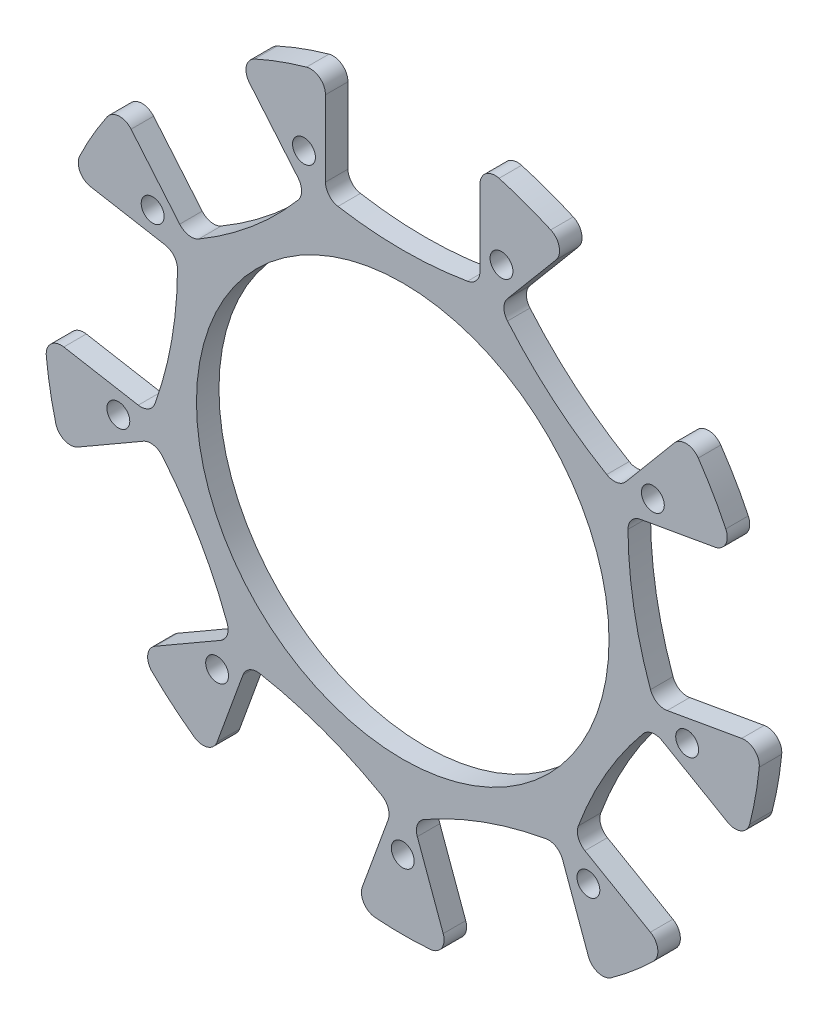
SolidWorks part; units mm, degrees
material "ｱｸﾘﾙ (中-上級の耐衝撃性)"
ref_plane "正面" through (0, 0, 0) normal (0, 0, 1) x (1, 0, 0)
ref_plane "平面" through (0, 0, 0) normal (0, 1, 0) x (1, 0, 0)
ref_plane "右側面" through (0, 0, 0) normal (1, 0, 0) x (0, 0, -1)
sketch "ｽｹｯﾁ1" plane through (0, 0, 0) normal (0, 0, 1) x (1, 0, 0)
  circle A0 centre (0, 0) radius 47.75
  dimension "D1" = 95.5
extrude "ﾎﾞｽ - 押し出し1" add sketch "ｽｹｯﾁ1" along normal blind 3
sketch "ｽｹｯﾁ2" plane through (0, 0, 3) normal (0, 0, 1) x (1, 0, 0)
  line L2 (0, 47.75) -> (0, -47.75) construction
  line L3 (-10.3, 46.6259) -> (-10.3, 32.3257)
  line L8 (22.0803, 42.3382) -> (12.8883, 31.3836)
  line L9 (37.8608, 29.0968) -> (28.6688, 18.1422)
  line L12 (10.3, 46.6259) -> (10.3, 32.3257)
  line L13 (0, 31.28) -> (0, 41.18) construction
  line L94 (44.1289, 18.24) -> (30.046, 15.7568)
  line L95 (47.7061, -2.047) -> (33.6232, -4.5302)
  line L96 (45.5292, -14.3929) -> (33.1449, -7.2428)
  line L97 (35.2292, -32.233) -> (22.8449, -25.0829)
  line L98 (25.6258, -40.2912) -> (20.7349, -26.8534)
  line L99 (6.2682, -47.3368) -> (1.3772, -33.899)
  line L100 (-6.2682, -47.3368) -> (-1.3772, -33.899)
  line L101 (-25.6258, -40.2912) -> (-20.7349, -26.8534)
  line L102 (-35.2292, -32.233) -> (-22.8449, -25.0829)
  line L103 (-45.5292, -14.3929) -> (-33.1449, -7.2428)
  line L104 (-47.7061, -2.047) -> (-33.6232, -4.5302)
  line L105 (-44.1289, 18.24) -> (-30.046, 15.7568)
  line L106 (-37.8608, 29.0968) -> (-28.6688, 18.1422)
  line L107 (-22.0803, 42.3382) -> (-12.8883, 31.3836)
  circle A0 centre (0, 0) radius 47.75 construction
  arc A1 (-10.3, 46.6259) -> (10.3, 46.6259) centre (0, 0) cw
  arc A2 (-10.3, 32.3257) -> (10.3, 32.3257) centre (0, 82.53) ccw
  arc A19 (22.0803, 42.3382) -> (37.8608, 29.0968) centre (0, 0) cw
  arc A20 (12.8883, 31.3836) -> (28.6688, 18.1422) centre (53.0493, 63.2216) ccw
  arc A21 (44.1289, 18.24) -> (47.7061, -2.047) centre (0, 0) cw
  arc A22 (30.046, 15.7568) -> (33.6232, -4.5302) centre (81.2762, 14.3312) ccw
  arc A23 (45.5292, -14.3929) -> (35.2292, -32.233) centre (0, 0) cw
  arc A24 (33.1449, -7.2428) -> (22.8449, -25.0829) centre (71.4731, -41.265) ccw
  arc A25 (25.6258, -40.2912) -> (6.2682, -47.3368) centre (0, 0) cw
  arc A26 (20.7349, -26.8534) -> (1.3772, -33.899) centre (28.2269, -77.5528) ccw
  arc A27 (-6.2682, -47.3368) -> (-25.6258, -40.2912) centre (0, 0) cw
  arc A28 (-1.3772, -33.899) -> (-20.7349, -26.8534) centre (-28.2269, -77.5528) ccw
  arc A29 (-35.2292, -32.233) -> (-45.5292, -14.3929) centre (0, 0) cw
  arc A30 (-22.8449, -25.0829) -> (-33.1449, -7.2428) centre (-71.4731, -41.265) ccw
  arc A31 (-47.7061, -2.047) -> (-44.1289, 18.24) centre (0, 0) cw
  arc A32 (-33.6232, -4.5302) -> (-30.046, 15.7568) centre (-81.2762, 14.3312) ccw
  arc A33 (-37.8608, 29.0968) -> (-22.0803, 42.3382) centre (0, 0) cw
  arc A34 (-28.6688, 18.1422) -> (-12.8883, 31.3836) centre (-53.0493, 63.2216) ccw
  point P11 (0, 41.18)
  point P58 (0, 0)
  dimension "D2" = 51.25
  dimension "D5" = 20.6
  dimension "D4" = 82.53
  dimension "D1" = 41.18
  dimension "D3" = 9.9
  dimension "D6" = 9
extrude "ｶｯﾄ - 押し出し1" cut sketch "ｽｹｯﾁ2" against normal through all
sketch "ｽｹｯﾁ3" plane through (0, 0, 3) normal (0, 0, 1) x (1, 0, 0)
  line L0 (0, 0) -> (0, -38.5) construction
  line L1 (0, 0) -> (-24.7473, -29.4927) construction
  line L2 (0, 0) -> (-37.9151, -6.6855) construction
  line L3 (0, 0) -> (-33.342, 19.25) construction
  line L4 (0, 0) -> (-13.1678, 36.1782) construction
  line L5 (0, 0) -> (13.1678, 36.1782) construction
  line L6 (0, 0) -> (33.342, 19.25) construction
  line L7 (0, 0) -> (37.9151, -6.6855) construction
  line L8 (0, 0) -> (24.7473, -29.4927) construction
  circle A2 centre (0, -38.5) radius 1.525
  circle A3 centre (0, 0) radius 38.5 construction
  circle A4 centre (-24.7473, -29.4927) radius 1.525
  circle A5 centre (0, 0) radius 38.5 construction
  circle A6 centre (-37.9151, -6.6855) radius 1.525
  circle A7 centre (0, 0) radius 38.5 construction
  circle A8 centre (-33.342, 19.25) radius 1.525
  circle A9 centre (0, 0) radius 38.5 construction
  circle A10 centre (-13.1678, 36.1782) radius 1.525
  circle A11 centre (0, 0) radius 38.5 construction
  circle A12 centre (13.1678, 36.1782) radius 1.525
  circle A13 centre (0, 0) radius 38.5 construction
  circle A14 centre (33.342, 19.25) radius 1.525
  circle A15 centre (0, 0) radius 38.5 construction
  circle A16 centre (37.9151, -6.6855) radius 1.525
  circle A17 centre (0, 0) radius 38.5 construction
  circle A18 centre (24.7473, -29.4927) radius 1.525
  circle A19 centre (0, 0) radius 38.5 construction
  point P10 (0, 0)
  point P32 (0, 0)
  dimension "D1" = 3.05
  dimension "D2" = 77
  dimension "D3" = 9
extrude "ｶｯﾄ - 押し出し2" cut sketch "ｽｹｯﾁ3" against normal through all
sketch "ｽｹｯﾁ4" plane through (0, 0, 0) normal (0, 0, -1) x (-1, 0, 0)
  circle A0 centre (0, 0) radius 27.5
  dimension "D1" = 55
extrude "ｶｯﾄ - 押し出し3" cut sketch "ｽｹｯﾁ4" against normal through all
fillet "ﾌｨﾚｯﾄ1" radius 2 36 edges at (33.1449, -7.2428, 1.5) (22.8449, -25.0829, 1.5) (35.2292, -32.233, 1.5) (45.5292, -14.3929, 1.5) (47.7061, -2.047, 1.5) (33.6232, -4.5302, 1.5) (44.1289, 18.24, 1.5) (30.046, 15.7568, 1.5) (37.8608, 29.0968, 1.5) (28.6688, 18.1422, 1.5) (12.8883, 31.3836, 1.5) (22.0803, 42.3382, 1.5) (10.3, 46.6259, 1.5) (10.3, 32.3257, 1.5) (-10.3, 32.3257, 1.5) (-10.3, 46.6259, 1.5) (-22.0803, 42.3382, 1.5) (-12.8883, 31.3836, 1.5) (-28.6688, 18.1422, 1.5) (-37.8608, 29.0968, 1.5) (-44.1289, 18.24, 1.5) (-30.046, 15.7568, 1.5) (-47.7061, -2.047, 1.5) (-33.6232, -4.5302, 1.5) (-45.5292, -14.3929, 1.5) (-33.1449, -7.2428, 1.5) (-22.8449, -25.0829, 1.5) (-35.2292, -32.233, 1.5) (-25.6258, -40.2912, 1.5) (-20.7349, -26.8534, 1.5) (-1.3772, -33.899, 1.5) (-6.2682, -47.3368, 1.5) (6.2682, -47.3368, 1.5) (1.3772, -33.899, 1.5) (20.7349, -26.8534, 1.5) (25.6258, -40.2912, 1.5)
